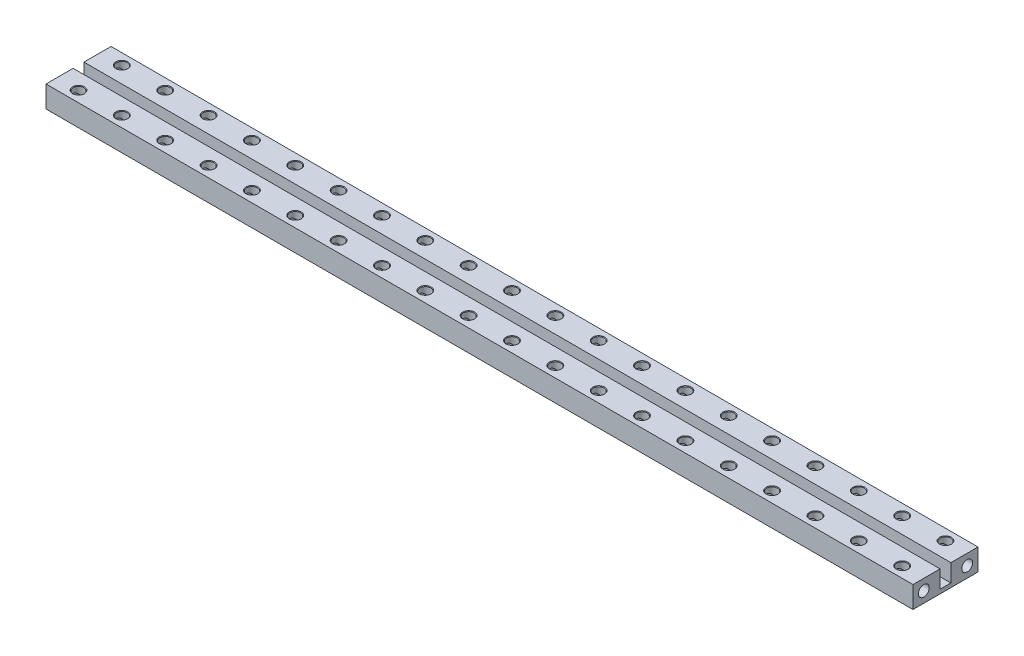
SolidWorks part; units mm, degrees
ref_plane "Front" through (0, 0, 0) normal (0, 0, 1) x (1, 0, 0)
ref_plane "Top" through (0, 0, 0) normal (0, 1, 0) x (1, 0, 0)
ref_plane "Right" through (0, 0, 0) normal (1, 0, 0) x (0, 0, -1)
sketch "草图1" plane through (0, 0, 0) normal (1, 0, 0) x (0, 0, -1)
  line L0 (14, 8) -> (24, 8)
  line L1 (0, 0) -> (24, 0)
  line L2 (0, 0) -> (0, 8)
  line L3 (0, 8) -> (10, 8)
  line L4 (24, 0) -> (24, 8)
  line L6 (10, 8) -> (10, 1.5)
  line L7 (10, 1.5) -> (14, 1.5)
  line L8 (14, 8) -> (14, 1.5)
  dimension "D1" = 8
  dimension "D2" = 24
  dimension "D3" = 6.5
  dimension "D4" = 10
  dimension "D5" = 4
extrude "凸台-拉伸1" add sketch "草图1" along normal blind 320
sketch "草图2" plane through (0, 8, 0) normal (0, 1, 0) x (1, 0, 0)
  line L0 (320, 24) -> (0, 24) construction
  line L1 (320, 0) -> (0, 0) construction
  line L3 (0, 24) -> (0, 14) construction
  line L4 (0, 10) -> (0, 0) construction
  circle A0 centre (8, 4) radius 2
  circle A1 centre (8, 20) radius 2
  circle A2 centre (24, 20) radius 2
  circle A3 centre (24, 4) radius 2
  circle A4 centre (40, 20) radius 2
  circle A5 centre (40, 4) radius 2
  circle A6 centre (56, 20) radius 2
  circle A7 centre (56, 4) radius 2
  circle A8 centre (72, 20) radius 2
  circle A9 centre (72, 4) radius 2
  circle A10 centre (88, 20) radius 2
  circle A11 centre (88, 4) radius 2
  circle A12 centre (104, 20) radius 2
  circle A13 centre (104, 4) radius 2
  circle A14 centre (120, 20) radius 2
  circle A15 centre (120, 4) radius 2
  circle A16 centre (136, 20) radius 2
  circle A17 centre (136, 4) radius 2
  circle A18 centre (152, 20) radius 2
  circle A19 centre (152, 4) radius 2
  circle A20 centre (168, 20) radius 2
  circle A21 centre (168, 4) radius 2
  circle A22 centre (184, 20) radius 2
  circle A23 centre (184, 4) radius 2
  circle A24 centre (200, 20) radius 2
  circle A25 centre (200, 4) radius 2
  circle A26 centre (216, 20) radius 2
  circle A27 centre (216, 4) radius 2
  circle A28 centre (232, 20) radius 2
  circle A29 centre (232, 4) radius 2
  circle A30 centre (248, 20) radius 2
  circle A31 centre (248, 4) radius 2
  circle A32 centre (264, 20) radius 2
  circle A33 centre (264, 4) radius 2
  circle A34 centre (280, 20) radius 2
  circle A35 centre (280, 4) radius 2
  circle A36 centre (296, 20) radius 2
  circle A37 centre (296, 4) radius 2
  circle A38 centre (312, 20) radius 2
  circle A39 centre (312, 4) radius 2
  dimension "D1" = 4
  dimension "D2" = 4
  dimension "D3" = 8
  dimension "D4" = 8
  dimension "D5" = 20
extrude "切除-拉伸1" cut sketch "草图2" against normal blind 320
chamfer "倒角1" distance 0.2 angle 45 80 edges at (312, 0, -18) (312, 0, -2) (312, 8, -2) (312, 8, -18) (168, 0, -18) (184, 0, -18) (136, 0, -18) (152, 0, -18) (232, 0, -18) (248, 0, -18) (200, 0, -18) (216, 0, -18) (40, 0, -18) (56, 0, -18) (8, 0, -18) (24, 0, -18) (104, 0, -18) (120, 0, -18) (72, 0, -18) (88, 0, -18) (296, 0, -18) (264, 0, -18) (280, 0, -18) (184, 0, -2) (200, 0, -2) (152, 0, -2) (168, 0, -2) (248, 0, -2) (264, 0, -2) (216, 0, -2) (232, 0, -2) (56, 0, -2) (72, 0, -2) (24, 0, -2) (40, 0, -2) (120, 0, -2) (136, 0, -2) (88, 0, -2) (104, 0, -2) (280, 0, -2) (296, 0, -2) (8, 0, -2) (8, 8, -2) (8, 8, -18) (24, 8, -2) (24, 8, -18) (40, 8, -2) (40, 8, -18) (56, 8, -2) (56, 8, -18) (72, 8, -2) (72, 8, -18) (88, 8, -2) (88, 8, -18) (104, 8, -2) (104, 8, -18) (120, 8, -2) (120, 8, -18) (136, 8, -2) (136, 8, -18) (152, 8, -2) (152, 8, -18) (168, 8, -2) (168, 8, -18) (184, 8, -2) (184, 8, -18) (200, 8, -2) (200, 8, -18) (216, 8, -2) (216, 8, -18) (232, 8, -2) (232, 8, -18) (248, 8, -2) (248, 8, -18) (264, 8, -2) (264, 8, -18) (280, 8, -2) (280, 8, -18) (296, 8, -2) (296, 8, -18)
sketch "草图3" plane through (0, 0, 0) normal (-1, 0, 0) x (0, 0, 1)
  line L0 (-24, 4) -> (-20, 4)
  line L1 (-24, 0) -> (-24, 8) construction
  line L2 (0, 4) -> (-4, 4)
  line L3 (0, 8) -> (0, 0) construction
  circle A0 centre (-20, 4) radius 2
  circle A1 centre (-4, 4) radius 2
extrude "切除-拉伸2" cut sketch "草图3" against normal through all contours A1 | A0
